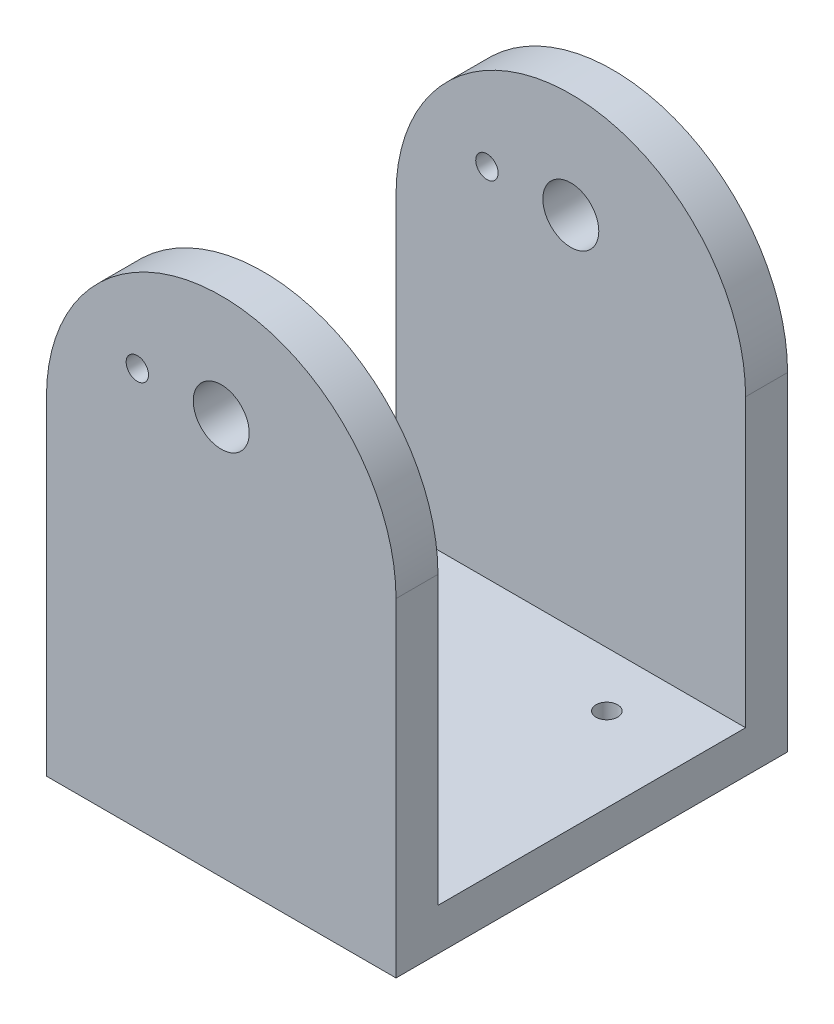
SolidWorks part; units mm, degrees
ref_plane "Alzado" through (0, 0, 0) normal (0, 0, 1) x (1, 0, 0)
ref_plane "Planta" through (0, 0, 0) normal (0, 1, 0) x (1, 0, 0)
ref_plane "Vista lateral" through (0, 0, 0) normal (1, 0, 0) x (0, 0, -1)
sketch "Croquis1" plane through (0, 0, 0) normal (0, 1, 0) x (1, 0, 0)
  line L1 (-25, -28) -> (25, -28)
  line L2 (-25, -28) -> (-25, 28)
  line L3 (-25, 28) -> (25, 28)
  line L4 (25, -28) -> (25, 28)
  line L5 (-25, -28) -> (25, 28) construction
  line L6 (-25, 28) -> (25, -28) construction
  point P0 (0, 0)
  dimension "D1" = 56
  dimension "D2" = 50
extrude "Saliente-Extruir1" add sketch "Croquis1" along normal blind 47
sketch "Croquis2" plane through (0, 0, 28) normal (0, 0, 1) x (1, 0, 0)
  line L0 (-25, 47) -> (25, 47) construction
  line L1 (-25, 47) -> (25, 47)
  arc A0 (25, 47) -> (-25, 47) centre (0, 47) ccw
extrude "Saliente-Extruir2" add sketch "Croquis2" against normal blind 56
sketch "Croquis3" plane through (-25, 0, 0) normal (-1, 0, 0) x (0, 0, 1)
  line L0 (-28, 0) -> (28, 0) construction
  line L2 (-22, 6) -> (22, 6)
  line L3 (22, 6) -> (22, 75.4776)
  line L4 (22, 75.4776) -> (-22, 75.4776)
  line L5 (-22, 75.4776) -> (-22, 6)
  line L6 (-28, 47) -> (-28, 0) construction
  line L7 (28, 47) -> (28, 0) construction
  dimension "D1" = 6
  dimension "D2" = 6
  dimension "D3" = 6
extrude "Cortar-Extruir1" cut sketch "Croquis3" against normal through all
sketch "Croquis4" plane through (0, 0, 28) normal (0, 0, 1) x (1, 0, 0)
  line L0 (0, 72) -> (0, 57) construction
  line L2 (-4, 57) -> (-12, 57) construction
  arc A0 (25, 47) -> (-25, 47) centre (0, 47) ccw construction
  circle A1 centre (0, 57) radius 4
  circle A3 centre (-12, 57) radius 1.6
  dimension "D2" = 8
  dimension "D6" = 3.2
  dimension "D1" = 15
  dimension "D5" = 8
extrude "Cortar-Extruir2" cut sketch "Croquis4" against normal through all
sketch "Croquis5" plane through (0, 6, 0) normal (0, 1, 0) x (1, 0, 0)
  line L0 (25, -14.15) -> (13, -14.15) construction
  line L1 (25, 22) -> (25, -22) construction
  line L3 (25, -22) -> (-25, -22) construction
  line L6 (25, 22) -> (-25, 22) construction
  line L7 (-25, 0) -> (-12, 0) construction
  line L8 (-25, 22) -> (-25, -22) construction
  circle A0 centre (13, -14.15) radius 1.55
  circle A1 centre (13, 14.15) radius 1.55
  circle A2 centre (-12, 0) radius 1.55
  dimension "D3" = 3.1
  dimension "D1" = 7.85
  dimension "D2" = 12
  dimension "D4" = 7.85
  dimension "D5" = 12
  dimension "D6" = 13
extrude "Cortar-Extruir3" cut sketch "Croquis5" against normal through all
